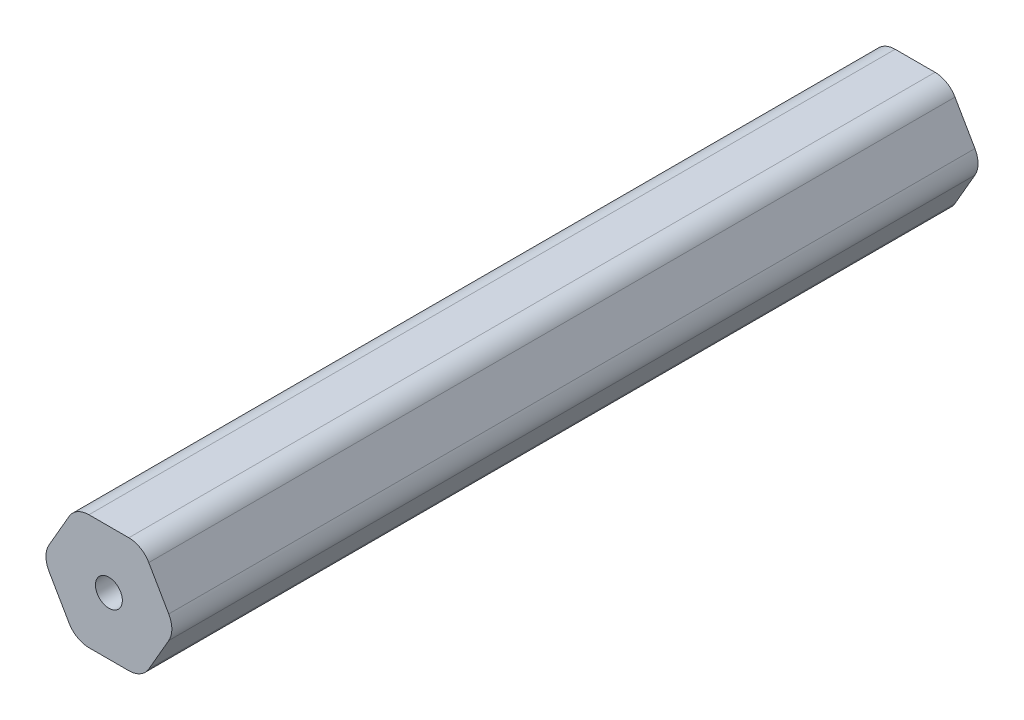
SolidWorks part; units mm, degrees
ref_plane "Front Plane" through (0, 0, 0) normal (0, 0, 1) x (1, 0, 0)
ref_plane "Top Plane" through (0, 0, 0) normal (0, 1, 0) x (1, 0, 0)
ref_plane "Right Plane" through (0, 0, 0) normal (1, 0, 0) x (0, 0, -1)
sketch "Sketch1" plane through (0, 0, 0) normal (0, 0, 1) x (1, 0, 0)
  line L1 (6.2737, -0.4509) -> (2.6075, 5.8991)
  line L2 (2.6075, 5.8991) -> (-4.7249, 5.8991)
  line L3 (-4.7249, 5.8991) -> (-8.391, -0.4509)
  line L4 (-8.391, -0.4509) -> (-4.7249, -6.8009)
  line L5 (-4.7249, -6.8009) -> (2.6075, -6.8009)
  line L6 (2.6075, -6.8009) -> (6.2737, -0.4509)
  circle A0 centre (-1.0587, -0.4509) radius 6.35 construction
  circle A1 centre (-1.0587, -0.4509) radius 1.4832
  dimension "D1" = 12.7
extrude "Boss-Extrude1" add sketch "Sketch1" along normal blind 88.9
fillet "Fillet1" radius 2.54 6 edges at (-8.391, -0.4509, 44.45) (-4.7249, 5.8991, 44.45) (-4.7249, -6.8009, 44.45) (2.6075, -6.8009, 44.45) (6.2737, -0.4509, 44.45) (2.6075, 5.8991, 44.45)
